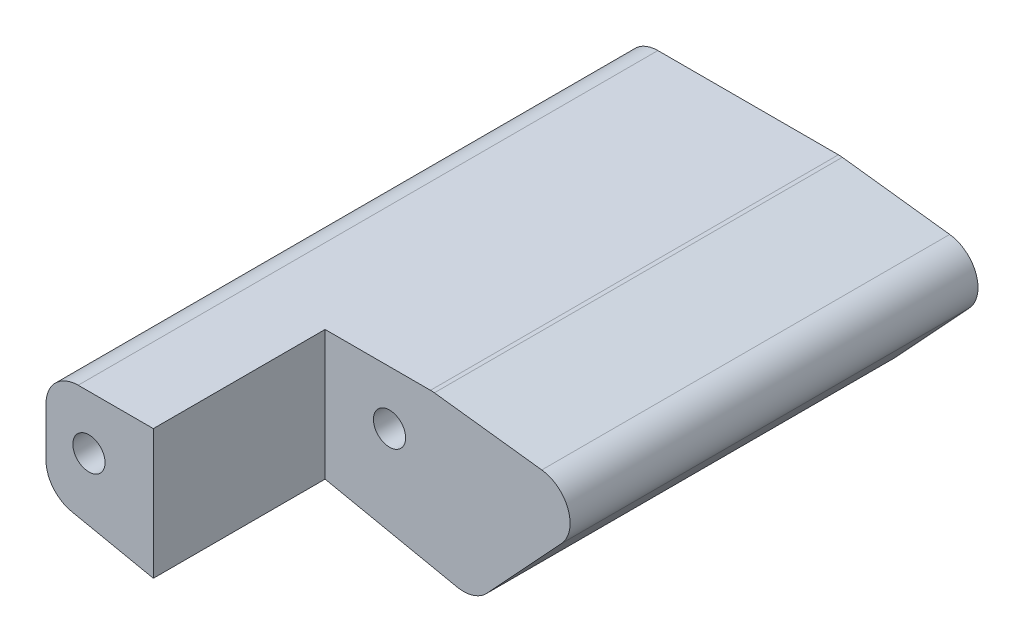
SolidWorks part; units mm, degrees
ref_plane "前视基准面" through (0, 0, 0) normal (0, 0, 1) x (1, 0, 0)
ref_plane "上视基准面" through (0, 0, 0) normal (0, 1, 0) x (1, 0, 0)
ref_plane "右视基准面" through (0, 0, 0) normal (1, 0, 0) x (0, 0, -1)
other "Configuration Table"
sketch "草图1" plane through (0, 0, 0) normal (0, 0, 1) x (1, 0, 0)
  line L0 (-6, 0) -> (6, 0) construction
  line L2 (-10, 5) -> (10, 5)
  line L3 (-10, 5) -> (-10, -5)
  line L4 (-10, -5) -> (10, -5)
  line L5 (10, 5) -> (10, -5)
  line L6 (-10, 5) -> (10, -5) construction
  line L7 (-10, -5) -> (10, 5) construction
  circle A0 centre (-6, 0) radius 1.5
  circle A1 centre (6, 0) radius 1.5
  point P4 (0, 0)
  point P7 (0, 0)
  dimension "D1" = 3
  dimension "D2" = 12
  dimension "D3" = 5
  dimension "D4" = 20
extrude "凸台-拉伸1" add sketch "草图1" along normal blind 54
sketch "草图2" plane through (0, 0, 0) normal (0, 0, -1) x (-1, 0, 0)
  line L0 (10, -5) -> (-13.9363, -9.9758)
  line L1 (-13.9363, -9.9758) -> (-26.0162, 3.0458)
  line L2 (-26.0162, 3.0458) -> (-10, 5)
  line L4 (-10, 5) -> (-10, -5)
  line L5 (-10, -5) -> (10, -5)
  line L6 (10, -5) -> (10, 5)
  line L7 (10, 5) -> (-10, 5)
  line L8 (-10, 5) -> (-10, -5)
  line L9 (-10, -5) -> (10, -5)
  line L10 (10, -5) -> (10, 5)
  line L11 (10, 5) -> (-10, 5)
  line M6 (-10, 5) -> (-10, -5)
  line M7 (-10, -5) -> (10, -5)
  dimension "D1" = 0
extrude "凸台-拉伸2" add sketch "草图2" against normal up to surface (54 mm away) contours L2 L1 L0 M7 M6 up to face at (-4.5, 0, 54)
fillet "圆角1" radius 3 5 edges at (10, 5, 27) (-10, 5, 27) (-10, -5, 27) (13.9363, -9.9758, 27) (26.0162, 3.0458, 27)
sketch "草图3" plane through (0, 5, 0) normal (0, 1, 0) x (1, 0, 0)
  line L0 (-1.5, -5.5) -> (-1.5, -48.5)
  line L1 (-1.5, -48.5) -> (4.3177, -48.5)
  line L2 (4.3177, -48.5) -> (4.3177, -5.5)
  line L3 (4.3177, -5.5) -> (-1.5, -5.5)
  line L4 (-7, -54) -> (9.8177, -54)
  line L5 (9.8177, -54) -> (9.8177, 0)
  line L6 (9.8177, 0) -> (-7, 0)
  line L7 (-7, 0) -> (-7, -54)
  line L8 (-7, -54) -> (9.8177, -54)
  line L9 (9.8177, -54) -> (9.8177, 0)
  line L10 (9.8177, 0) -> (-7, 0)
  line L11 (-7, 0) -> (-7, -54)
  line L12 (-1.5, -10.5) -> (4.3177, -10.5)
  line L13 (-1.5, -43.5) -> (4.3177, -43.5)
  line L14 (-1.5, -27) -> (4.3177, -27)
  dimension "D3" = 5
  dimension "D4" = 5
  dimension "D1" = 0
  dimension "D2" = 5.5
sketch "草图4" plane through (0, 0, 54) normal (0, 0, 1) x (1, 0, 0)
  line L0 (0, 5) -> (0, -7.0788)
  line L1 (-7.6106, -5.4967) -> (12.2782, -9.6311) construction
  line L5 (20.1849, 3.7573) -> (10.181, 4.9779)
  line L6 (9.8177, 5) -> (-7, 5)
  line L7 (-10, 2) -> (-10, -2.5595)
  line L8 (-7.6106, -5.4967) -> (12.2782, -9.6311)
  line L9 (15.0881, -8.7342) -> (22.0209, -1.261)
  line L10 (20.1849, 3.7573) -> (10.181, 4.9779)
  line L11 (9.8177, 5) -> (-7, 5)
  line L12 (-10, 2) -> (-10, -2.5595)
  line L13 (-7.6106, -5.4967) -> (12.2782, -9.6311)
  line L14 (15.0881, -8.7342) -> (22.0209, -1.261)
  arc A5 (10.181, 4.9779) -> (9.8177, 5) centre (9.8177, 2) ccw
  arc A6 (-7, 5) -> (-10, 2) centre (-7, 2) ccw
  arc A7 (-10, -2.5595) -> (-7.6106, -5.4967) centre (-7, -2.5595) ccw
  arc A8 (12.2782, -9.6311) -> (15.0881, -8.7342) centre (12.8888, -6.6939) ccw
  arc A9 (22.0209, -1.261) -> (20.1849, 3.7573) centre (19.8216, 0.7794) ccw
  arc A10 (10.181, 4.9779) -> (9.8177, 5) centre (9.8177, 2) ccw
  arc A11 (-7, 5) -> (-10, 2) centre (-7, 2) ccw
  arc A12 (-10, -2.5595) -> (-7.6106, -5.4967) centre (-7, -2.5595) ccw
  arc A13 (12.2782, -9.6311) -> (15.0881, -8.7342) centre (12.8888, -6.6939) ccw
  arc A14 (22.0209, -1.261) -> (20.1849, 3.7573) centre (19.8216, 0.7794) ccw
  point P12 (0, -7.0788)
  line M11 (20.1849, 3.7573) -> (10.181, 4.9779)
  arc M12 (10.181, 4.9779) -> (9.8177, 5) centre (9.8177, 2) ccw
  line M13 (9.8177, 5) -> (-7, 5)
  line M17 (-7.6106, -5.4967) -> (12.2782, -9.6311)
  arc M18 (12.2782, -9.6311) -> (15.0881, -8.7342) centre (12.8888, -6.6939) ccw
  line M19 (15.0881, -8.7342) -> (22.0209, -1.261)
  arc M20 (22.0209, -1.261) -> (20.1849, 3.7573) centre (19.8216, 0.7794) ccw
  circle M22 centre (6, 0) radius 1.5
  dimension "D1" = 0
extrude "切除-拉伸2" cut sketch "草图4" against normal blind 16 contours L0 M13 M17 M18 M19 M20 M11 M12 M22
